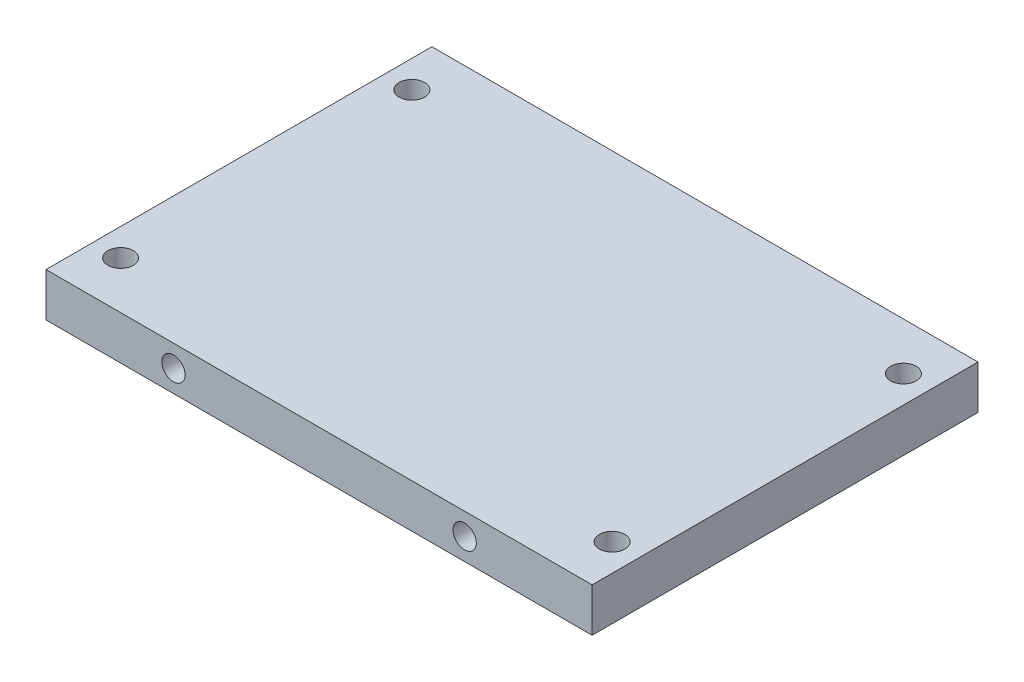
SolidWorks part; units mm, degrees
other "Markup1"
sketch "Sketch5" plane through (75, 6, 0) normal (0.0216, 0.9138, -0.4056) x (-0.9986, 0, -0.0531)
ref_plane "Front Plane" through (0, 0, 0) normal (0, 0, 1) x (1, 0, 0)
ref_plane "Top Plane" through (0, 0, 0) normal (0, 1, 0) x (1, 0, 0)
ref_plane "Right Plane" through (0, 0, 0) normal (1, 0, 0) x (0, 0, -1)
sketch "Sketch1" plane through (0, 0, 0) normal (0, 1, 0) x (1, 0, 0)
  line L0 (37.5, 0) -> (37.5, -26.5) construction
  line L1 (0, 0) -> (2.8486, 0)
  line L2 (0, 0) -> (0, -53)
  line L3 (0, -53) -> (2.8486, -53)
  line L4 (75, 0) -> (75, -53)
  line L5 (75, 3.5) -> (71.25, 3.5) construction
  line L7 (0, 0) -> (0, -53)
  line L9 (75, 0) -> (75, -53)
  line L10 (0, 3.5) -> (75, -56.5) construction
  line L11 (0, -56.5) -> (75, 3.5) construction
  line L12 (71.25, 3.5) -> (71.25, -6.5) construction
  line L13 (37.5, -26.5) -> (75, -26.5) construction
  line L14 (4.6514, -53) -> (70.3486, -53)
  line L15 (4.6514, 0) -> (70.3486, 0)
  line L16 (72.1514, 0) -> (75, 0)
  line L17 (72.1514, -53) -> (75, -53)
  line L18 (0, 0) -> (75, 0)
  line L19 (0, -53) -> (75, -53)
  circle A4 centre (71.25, -6.5) radius 1.75
  circle A5 centre (3.75, -6.5) radius 1.75
  circle A6 centre (71.25, -46.5) radius 1.75
  circle A7 centre (3.75, -46.5) radius 1.75
  point P12 (27.5, 15)
  point P18 (32.25, 15)
  point P28 (0, 0)
  point P32 (0, 0)
  dimension "D5" = 10
  dimension "D6" = 3.5
  dimension "D1" = 26.5
  dimension "D2" = 53
  dimension "D3" = 60
  dimension "D4" = 3.75
extrude "Boss-Extrude8" add sketch "Sketch1" along normal blind 6 contours A7 L14 A6 L17 L4 L16 A4 L15 A5 L1 L2 L3
sketch "Sketch6" plane through (0, 0, 0) normal (0, 0, -1) x (-1, 0, 0)
  line L0 (-37.5, 6) -> (-37.5, 0) construction
  line L1 (0, 6) -> (-75, 6) construction
  line L2 (0, 0) -> (-75, 0) construction
  line L3 (-57.5, 3) -> (-17.5, 3) construction
  circle A0 centre (-57.5, 3) radius 1.6
  circle A1 centre (-17.5, 3) radius 1.6
  point P8 (-37.5, 3)
  point P9 (-37.5, 3)
  dimension "D2" = 3.2
  dimension "D1" = 40
extrude "Cut-Extrude2" cut sketch "Sketch6" against normal blind 5
sketch "Sketch7" plane through (0, 6, 0) normal (0, 1, 0) x (1, 0, 0)
  line L0 (75, -26.5) -> (0, -26.5) construction
  line L1 (75, 0) -> (75, -53) construction
  line L2 (0, 0) -> (0, -53) construction
ref_plane "Plane1" through (0, 0, 26.5) normal (0, 0, 1) x (1, 0, 0)
mirror "Mirror1" about plane through (0, 0, 26.5) normal (0, 0, 1) of "Cut-Extrude2"
